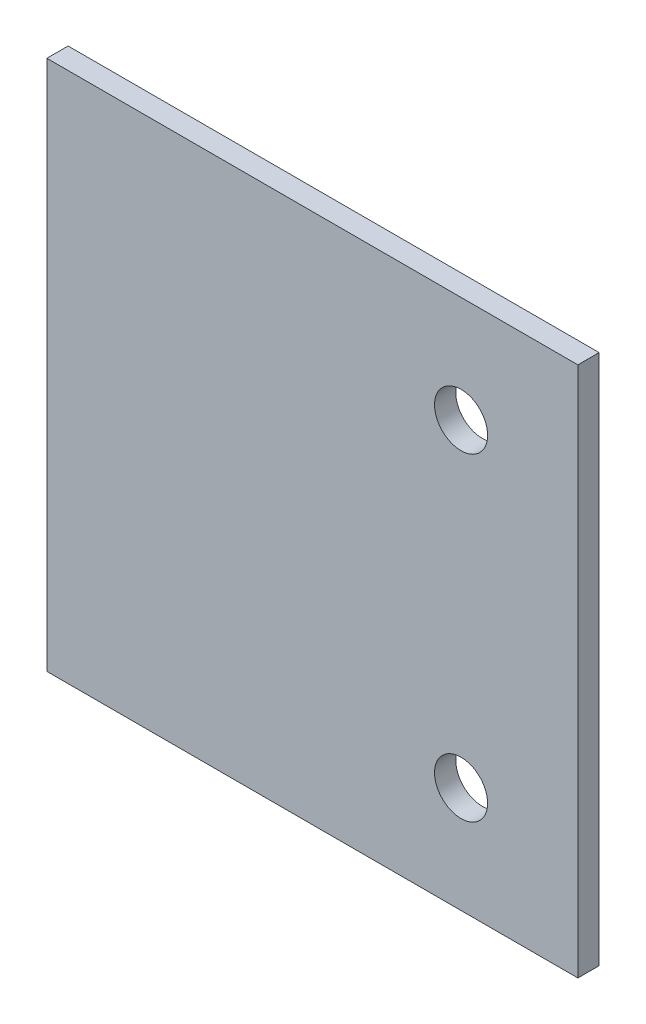
SolidWorks part; units mm, degrees
ref_plane "前视基准面" through (0, 0, 0) normal (0, 0, 1) x (1, 0, 0)
ref_plane "上视基准面" through (0, 0, 0) normal (0, 1, 0) x (1, 0, 0)
ref_plane "右视基准面" through (0, 0, 0) normal (1, 0, 0) x (0, 0, -1)
other "Configuration Table"
sketch "草图2" plane through (0, 0, 0) normal (0, 0, 1) x (1, 0, 0)
  line L1 (-25, -25) -> (25, -25)
  line L2 (-25, -25) -> (-25, 25)
  line L3 (-25, 25) -> (25, 25)
  line L4 (25, -25) -> (25, 25)
  line L5 (-25, -25) -> (25, 25) construction
  line L6 (-25, 25) -> (25, -25) construction
  point P0 (0, 0)
  dimension "D1" = 50
  dimension "D2" = 50
extrude "凸台-拉伸1" add sketch "草图2" along normal blind 2
sketch "草图4" plane through (0, 0, 2) normal (0, 0, 1) x (1, 0, 0)
  line L0 (14, 25) -> (14, -25) construction
  line L1 (25, 25) -> (-25, 25) construction
  line L2 (-25, -25) -> (25, -25) construction
  line L3 (25, -25) -> (25, 25) construction
  circle A0 centre (14, -15) radius 2.5
  circle A1 centre (14, 15) radius 2.5
  point P10 (13.54, 15)
  dimension "D3" = 5
  dimension "D1" = 30
  dimension "D2" = 10
  dimension "D4" = 11
extrude "切除-拉伸1" cut sketch "草图4" against normal up to surface (2 mm away) up to face at (0, 0, 0)
